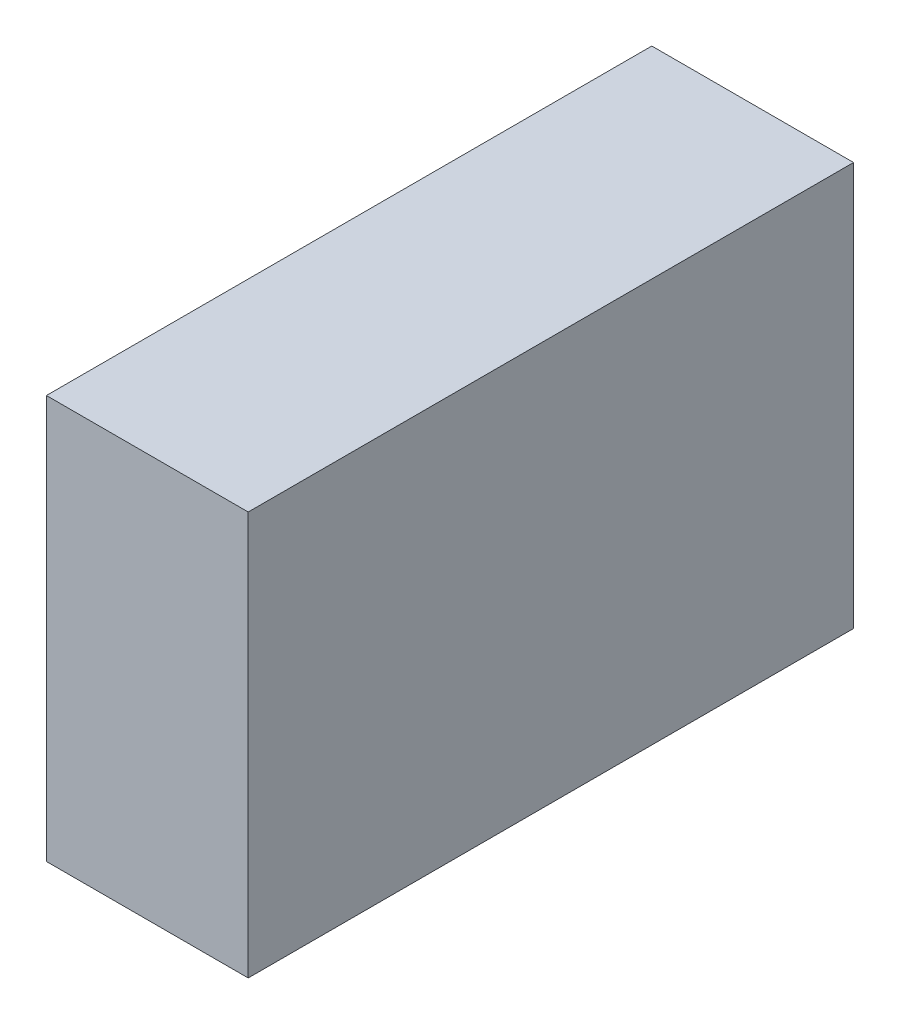
SolidWorks part; units mm, degrees
ref_plane "Front Plane" through (0, 0, 0) normal (0, 0, 1) x (1, 0, 0)
ref_plane "Top Plane" through (0, 0, 0) normal (0, 1, 0) x (1, 0, 0)
ref_plane "Right Plane" through (0, 0, 0) normal (1, 0, 0) x (0, 0, -1)
sketch "Sketch2" plane through (0, 0, 0) normal (0, 0, 1) x (1, 0, 0)
  line L1 (-25, 50) -> (25, 50)
  line L2 (-25, 50) -> (-25, -50)
  line L3 (-25, -50) -> (25, -50)
  line L4 (25, 50) -> (25, -50)
  dimension "block_length" = 50
  dimension "D1" = 25
  dimension "D2" = 50
  dimension "block_width" = 100
extrude "Boss-Extrude1" add sketch "Sketch2" along normal blind 150
equation "\"D1@Sketch2\" = \"block_length@Sketch2\" / 2"
equation "\"D2@Sketch2\"=\"block_width@Sketch2\"/2"
